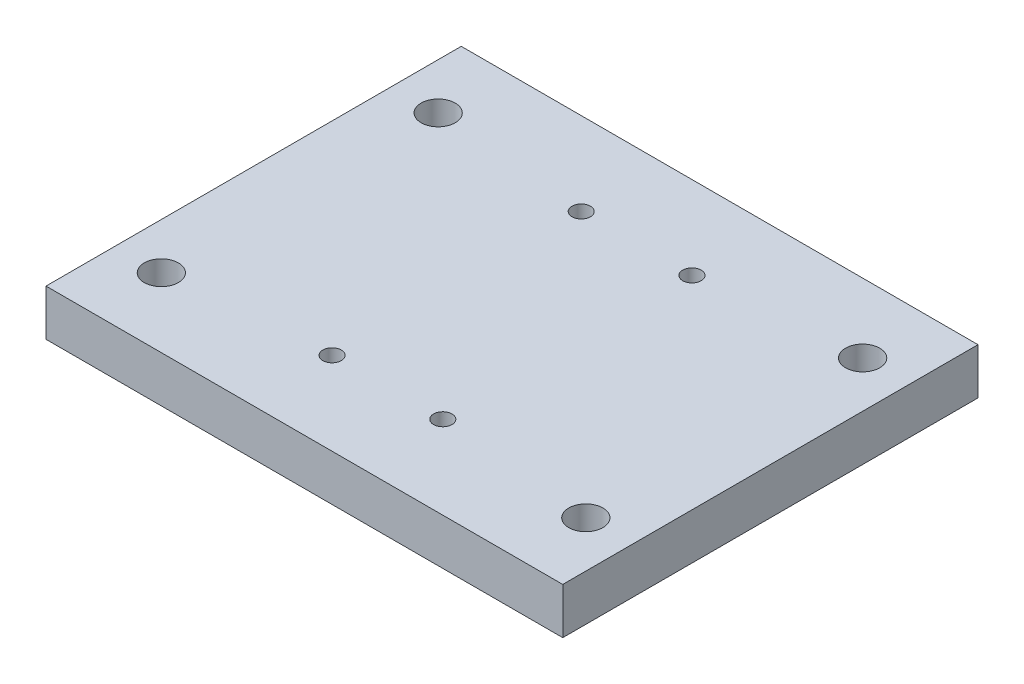
SolidWorks part; units mm, degrees
ref_plane "Front Plane" through (0, 0, 0) normal (0, 0, 1) x (1, 0, 0)
ref_plane "Top Plane" through (0, 0, 0) normal (0, 1, 0) x (1, 0, 0)
ref_plane "Right Plane" through (0, 0, 0) normal (1, 0, 0) x (0, 0, -1)
sketch "Sketch2" plane through (0, 0, 0) normal (0, 1, 0) x (1, 0, 0)
  line L1 (0, 0) -> (56, 0)
  line L2 (0, 0) -> (0, 45)
  line L3 (0, 45) -> (56, 45)
  line L4 (56, 0) -> (56, 45)
  dimension "D1" = 56
  dimension "D2" = 45
extrude "Boss-Extrude1" add sketch "Sketch2" along normal blind 5
sketch "Sketch3" plane through (0, 5, 0) normal (0, 1, 0) x (1, 0, 0)
  line L0 (28, 0) -> (28, 45)
  line L1 (0, 0) -> (56, 0) construction
  line L2 (56, 45) -> (0, 45) construction
  line L3 (0, 22.5) -> (56, 22.5)
  line L4 (0, 45) -> (0, 0) construction
  line L5 (56, 0) -> (56, 45) construction
  circle A0 centre (5, 37.5) radius 1.85
  circle A1 centre (51, 37.5) radius 1.85
  circle A2 centre (5, 7.5) radius 1.85
  circle A3 centre (51, 7.5) radius 1.85
  point P14 (0, 0)
  point P15 (0, 0)
  point P22 (0, 0)
  point P23 (0, 0)
  dimension "D1" = 3.7
  dimension "D2" = 3.7
  dimension "D3" = 3.7
  dimension "D4" = 3.7
  dimension "D5" = 46
  dimension "D6" = 23
  dimension "D7" = 30
  dimension "D8" = 15
extrude "Cut-Extrude1" cut sketch "Sketch3" against normal blind 3 contours A0 | A1 | A3 | A2
sketch "Sketch4" plane through (0, 5, 0) normal (0, 1, 0) x (1, 0, 0)
  line L0 (0, 22.5) -> (56, 22.5)
  line L1 (0, 45) -> (0, 0) construction
  line L2 (56, 0) -> (56, 45) construction
  line L3 (0, 0) -> (56, 0) construction
  line L4 (28, 45) -> (28, 0)
  line L5 (56, 45) -> (0, 45) construction
  circle A0 centre (22, 36) radius 1
  circle A1 centre (34, 36) radius 1
  circle A2 centre (34, 9) radius 1
  circle A3 centre (22, 9) radius 1
  point P20 (0, 0)
  point P21 (0, 0)
  point P22 (0, 0)
  dimension "D1" = 2
  dimension "D2" = 2
  dimension "D3" = 2
  dimension "D4" = 2
  dimension "D5" = 12
  dimension "D6" = 6
  dimension "D7" = 27
  dimension "D8" = 13.5
extrude "Cut-Extrude2" cut sketch "Sketch4" against normal blind 5 contours A0 | A3 | A2 | A1
